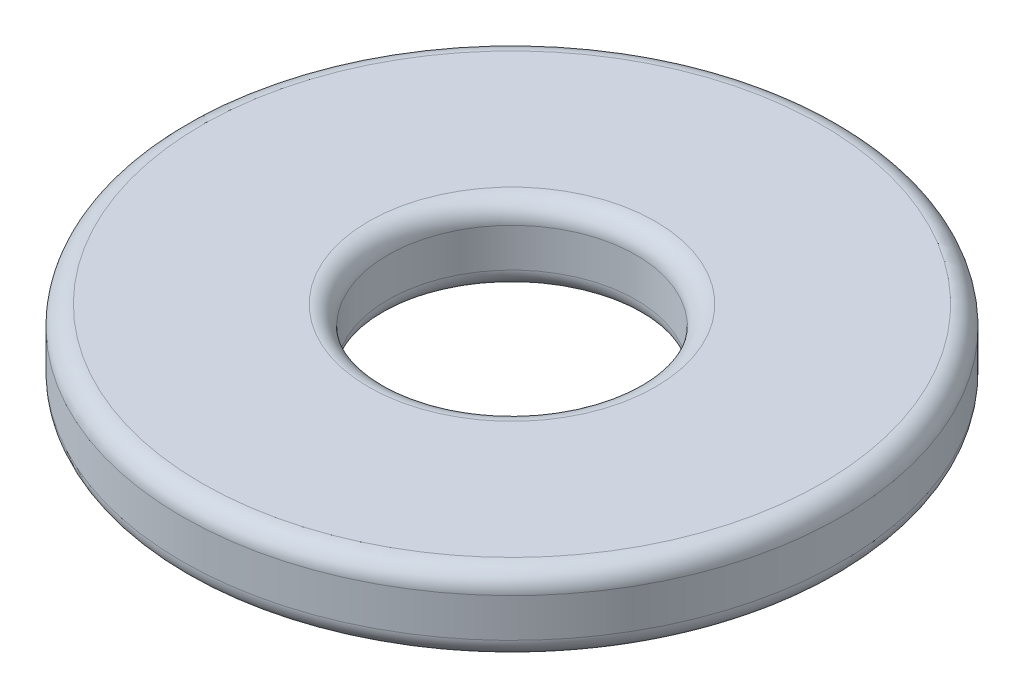
SolidWorks part; units mm, degrees
ref_plane "Front Plane" through (0, 0, 0) normal (0, 0, 1) x (1, 0, 0)
ref_plane "Top Plane" through (0, 0, 0) normal (0, 1, 0) x (1, 0, 0)
ref_plane "Right Plane" through (0, 0, 0) normal (1, 0, 0) x (0, 0, -1)
sketch "Sketch1" plane through (0, 0, 0) normal (0, 1, 0) x (1, 0, 0)
  circle A0 centre (0, 0) radius 4.25
  circle A1 centre (0, 0) radius 1.6
  dimension "D1" = 8.5
  dimension "D2" = 3.2
extrude "Boss-Extrude1" add sketch "Sketch1" along normal blind 1 contours A0 A1
fillet "Fillet1" radius 0.25 2 edges at (0, 0, 4.25) (0, 1, 4.25)
fillet "Fillet2" radius 0.25 2 edges at (0, 1, 1.6) (0, 0, 1.6)
